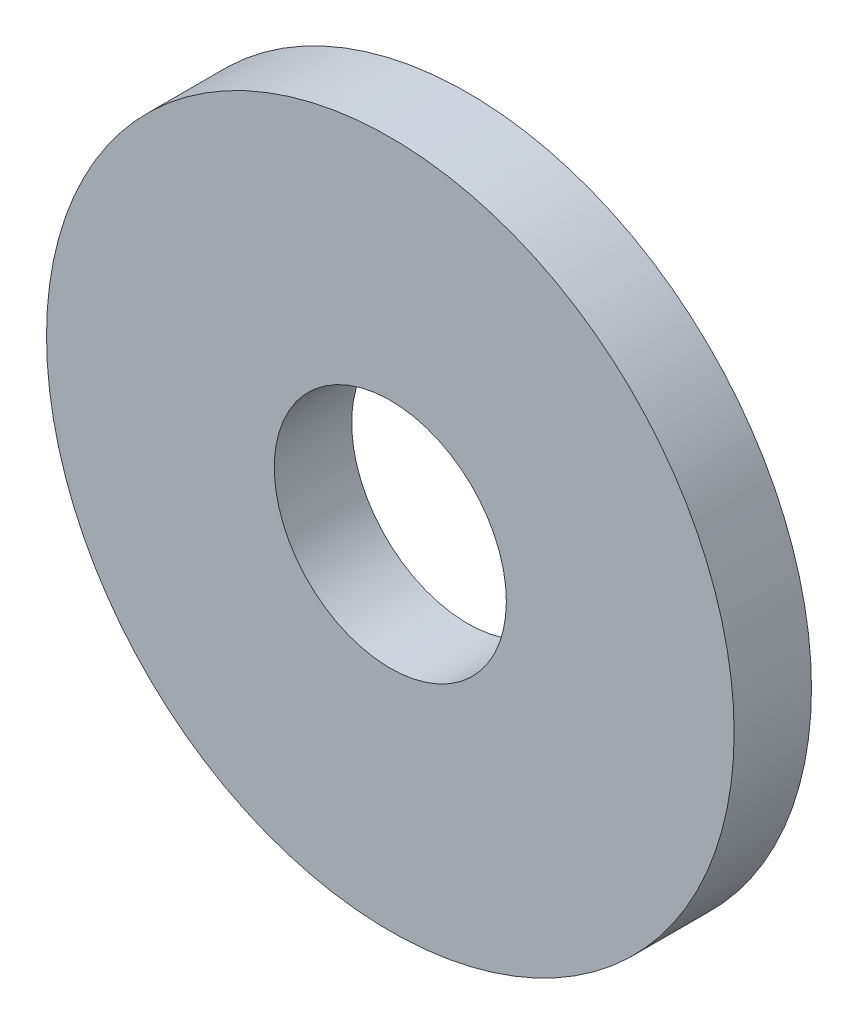
SolidWorks part; units mm, degrees
ref_plane "Front Plane" through (0, 0, 0) normal (0, 0, 1) x (1, 0, 0)
ref_plane "Top Plane" through (0, 0, 0) normal (0, 1, 0) x (1, 0, 0)
ref_plane "Right Plane" through (0, 0, 0) normal (1, 0, 0) x (0, 0, -1)
sketch "Sketch1" plane through (0, 0, 0) normal (0, 0, 1) x (1, 0, 0)
  circle A0 centre (0, 0) radius 4
  circle A1 centre (0, 0) radius 1.35
  dimension "OD" = 8
  dimension "ID1" = 2.7
extrude "Boss-Extrude1" add sketch "Sketch1" along normal blind 0.9
